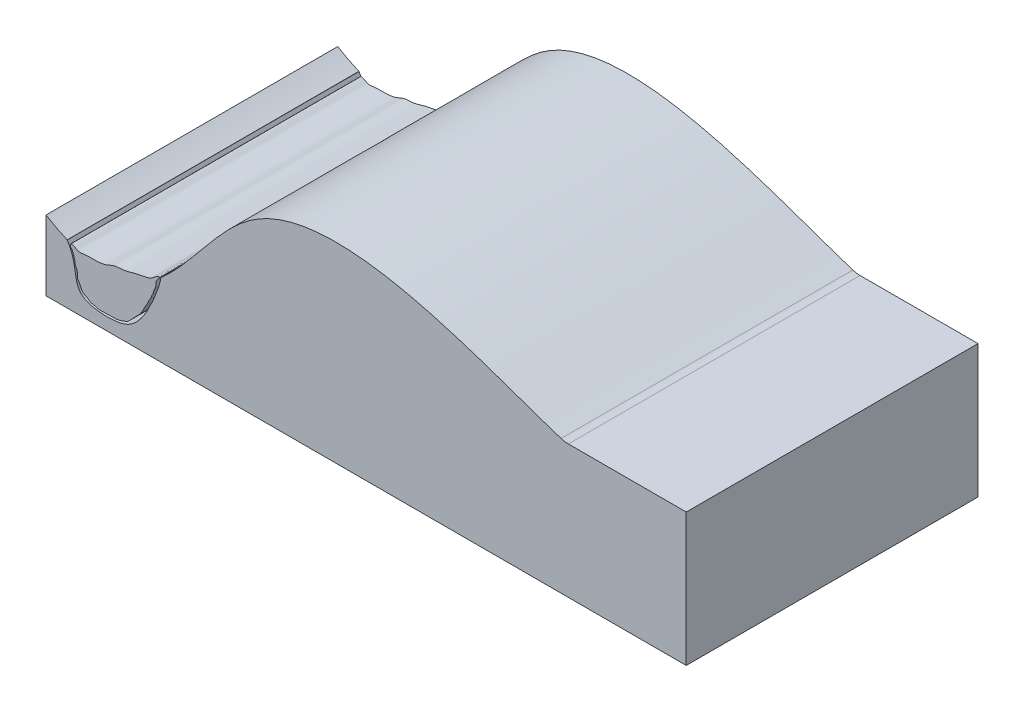
SolidWorks part; units mm, degrees
ref_plane "Front Plane" through (0, 0, 0) normal (0, 0, 1) x (1, 0, 0)
ref_plane "Top Plane" through (0, 0, 0) normal (0, 1, 0) x (1, 0, 0)
ref_plane "Right Plane" through (0, 0, 0) normal (1, 0, 0) x (0, 0, -1)
sketch "Sketch1" plane through (0, 0, 0) normal (0, 1, 0) x (1, 0, 0)
  line L1 (0, 0) -> (390144, 0)
  line L2 (0, 0) -> (0, 219456)
  line L3 (0, 219456) -> (390144, 219456)
  line L4 (390144, 0) -> (390144, 219456)
  dimension "D1" = 219456
  dimension "D2" = 390144
extrude "Boss-Extrude1" add sketch "Sketch1" along normal blind 163624.768
sketch "Sketch3" plane through (0, 0, 0) normal (0, 0, 1) x (1, 0, 0)
  line L0 (0, 163624.768) -> (0, 0) construction
  line L1 (390144, 163624.768) -> (390144, 0) construction
  line L2 (0, 52667.8814) -> (0, 163624.768)
  line L3 (0, 163624.768) -> (390144, 163624.768)
  line L4 (390144, 163624.768) -> (390144, 99964.3642)
  line L5 (0, 163624.768) -> (390144, 163624.768)
  line L6 (390144, 163624.768) -> (390144, 99964.3642)
  spline S0 degree 3 poles (0, 52667.8814) (83559.6572, 2393.5525) (133616.2869, 210787.4727) (330012.5481, 118598.2128) (390144, 99964.3642) knots 0 0 0 0 0.441082 1 1 1 1
  line M2 (390144, 0) -> (390144, 163624.768)
  line M3 (390144, 163624.768) -> (0, 163624.768)
  line M4 (0, 163624.768) -> (0, 0)
extrude "Cut-Extrude2" cut sketch "Sketch3" against normal blind 271472.66 contours S0 M4 M2 M3
sketch "Sketch5" plane through (0, 0, 0) normal (0, 0, 1) x (1, 0, 0)
  spline S0 degree 3 poles (14431.7496, 46625.0993) (24201.7274, 32802.4265) (17610.9448, 11877.3009) (53463.0961, 7585.1835) (74840.7565, 15824.6682) (91313.9035, 64441.1489) (81506.8274, 54111.2603) (76367.1066, 50845.029) (68202.5033, 44982.044) (56865.2682, 41044.1306) (45351.2439, 39680.8731) (35439.5273, 39718.4686) (25773.1918, 42444.452) (20914.1159, 42940.036) (14431.7496, 46625.0993) (24201.7274, 32802.4265) (17610.9448, 11877.3009) knots -0.072799 -0.020591 -0.008866 0 0.165559 0.282229 0.438504 0.60852 0.616398 0.649042 0.704919 0.771328 0.833559 0.884173 0.927201 0.979409 0.991134 1 1.165559 1.282229 1.438504 only from (15943.9389, 44438.8015) to (15943.9389, 44438.8015)
  spline S1 degree 3 poles (0, 52667.8814) (83559.6572, 2393.5525) (133616.2869, 210787.4727) (330012.5481, 118598.2128) (390144, 99964.3642) knots 0 0 0 0 0.441082 1 1 1 1 construction
extrude "Cut-Extrude3" cut sketch "Sketch5" against normal blind 346295.98
sketch "Sketch7" plane through (0, 0, 0) normal (0, 0, 1) x (1, 0, 0)
  spline S0 degree 3 poles (18070.7866, 41127.0455) (18475.304, 45139.2518) (23962.7542, 40353.9665) (30183.9147, 41954.9182) (37537.5175, 41407.4955) (45520.1415, 42410.2061) (51483.2006, 45890.3031) (58555.2407, 45493.8791) (65378.1529, 47875.2527) (72346.0519, 49244.944) (78836.8329, 50436.598) (81449.8345, 53125.8908) (86286.384, 55943.7922) (84079.8289, 52690.5613) (82687.65, 51130.4422) (82652.2091, 48852.6132) (82536.5595, 46912.3623) (81786.1816, 45027.4305) (80694.0976, 43387.6648) (80640.1147, 41164.4278) (79194.0938, 39860.4057) (79031.075, 37598.4746) (76995.7119, 35793.4659) (76552.9934, 32965.4592) (74618.2785, 30683.6431) (73690.9639, 28196.4723) (72158.7839, 25747.5678) (70755.1439, 23302.3136) (68431.7918, 21204.45) (66260.0756, 18679.896) (63729.2648, 16312.8745) (61435.8295, 13764.8995) (57894.7692, 12644.0029) (54454.2648, 11179.5325) (50672.1846, 11282.3295) (47077.0138, 11118.5374) (43379.5184, 11131.826) (39786.7281, 10843.9441) (36520.9118, 12108.4124) (33326.8487, 12299.9786) (30638.8272, 14774.5948) (27304.7137, 15781.2384) (26082.9072, 19021.3828) (25051.1583, 21270.8785) (23527.9885, 23006.2055) (23757.7905, 24769.5225) (23527.0895, 26476.9018) (23660.2443, 27985.5434) (22878.4594, 28895.86) (22873.704, 29744.9816) (22343.2117, 30428.7306) (21873.2078, 31131.156) (21931.726, 31903.5383) (22007.1644, 32713.1135) (21621.4709, 33635.4798) (21460.4638, 34502.1711) (21115.2633, 35254.8343) (21089.9604, 36107.5251) (20759.1419, 37218.3683) (20297.876, 38469.1216) (19537.7374, 39469.7636) (19282.2146, 40516.7158) (18070.7866, 41127.0455) (18475.304, 45139.2518) (23962.7542, 40353.9665) knots -0.020243 -0.015668 -0.009755 0 0.032228 0.056849 0.110768 0.150328 0.188551 0.220725 0.264217 0.305585 0.341894 0.362148 0.381063 0.393337 0.405061 0.419121 0.427996 0.437402 0.452166 0.459728 0.472635 0.481314 0.495358 0.514512 0.526236 0.543895 0.557839 0.573945 0.590044 0.609107 0.628816 0.647565 0.664218 0.689048 0.708581 0.725776 0.748543 0.769917 0.783892 0.805976 0.820021 0.842967 0.858762 0.873929 0.884764 0.894531 0.901514 0.913734 0.91748 0.920305 0.927164 0.931319 0.933642 0.939681 0.944531 0.949828 0.954235 0.95798 0.963726 0.973303 0.979757 0.984332 0.990245 1 1.032228 1.056849 1.110768 only from (18453.1204, 42903.9944) to (18453.1204, 42903.9944)
extrude "Boss-Extrude10" add sketch "Sketch7" against normal blind 217957.146 separate body
fillet "Fillet2" radius 381 2 edges at (86418.1627, 55180.787, -109728) (15943.9389, 44438.8015, -109728)
sketch3d "3DSketch1"
  line L1 (390144, 99964.3642, 0) -> (390144, 99964.3642, -219456)
  line L2 (390144, 99964.3642, 0) -> (390144, 0, 0)
  line L3 (390144, 0, 0) -> (390144, 0, -219456)
  line L4 (390144, 99964.3642, -219456) -> (390144, 0, -219456)
extrude "Boss-Extrude11" add sketch "3DSketch1" along direction (-1, 0, 0) on the side of the normal blind 91440
fillet "Fillet5" radius 17983.2 1 edges
